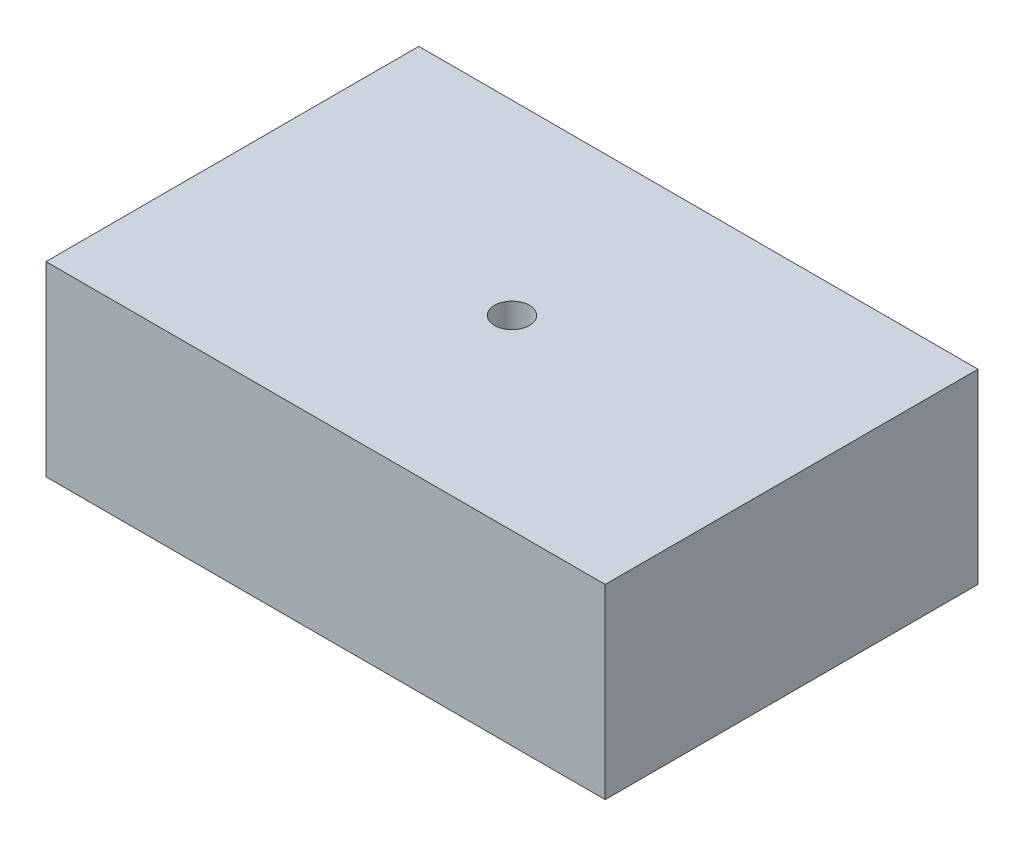
SolidWorks part; units mm, degrees
ref_plane "Front Plane" through (0, 0, 0) normal (0, 0, 1) x (1, 0, 0)
ref_plane "Top Plane" through (0, 0, 0) normal (0, 1, 0) x (1, 0, 0)
ref_plane "Right Plane" through (0, 0, 0) normal (1, 0, 0) x (0, 0, -1)
sketch "Sketch1" plane through (0, 0, 0) normal (0, 1, 0) x (1, 0, 0)
  line L1 (0, 0) -> (76.2, 0)
  line L2 (0, 0) -> (0, -50.8)
  line L3 (0, -50.8) -> (76.2, -50.8)
  line L4 (76.2, 0) -> (76.2, -50.8)
  circle A0 centre (38.1, -25.4) radius 2.3812
extrude "Boss-Extrude1" add sketch "Sketch1" along normal blind 25.4
